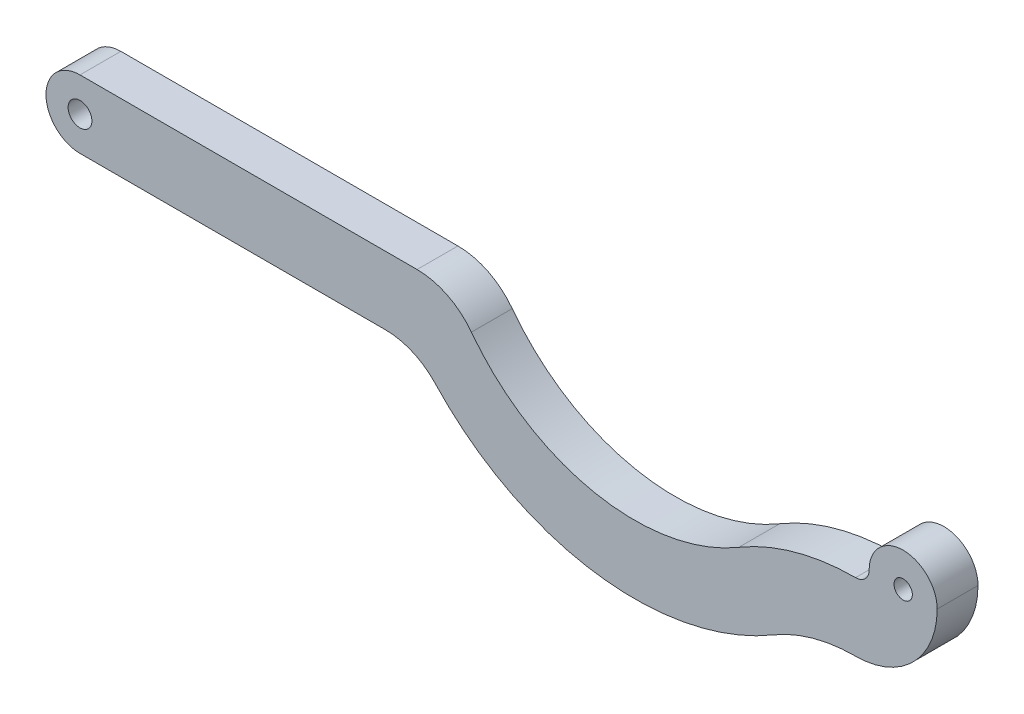
SolidWorks part; units mm, degrees
ref_plane "Plan de face" through (0, 0, 0) normal (0, 0, 1) x (1, 0, 0)
ref_plane "Plan de dessus" through (0, 0, 0) normal (0, 1, 0) x (1, 0, 0)
ref_plane "Plan de droite" through (0, 0, 0) normal (1, 0, 0) x (0, 0, -1)
sketch "Esquisse1" plane through (0, 0, 0) normal (0, 0, 1) x (1, 0, 0)
  line L0 (113.4531, 0) -> (121, 0) construction
  line L1 (0, 0) -> (49.5469, 0)
  line L2 (0, 0) -> (0, 10) construction
  line L3 (0, 10) -> (55, 10)
  line L4 (121, 0) -> (121, 10) construction
  line L5 (108, 10) -> (121, 10) construction
  line L6 (121, 5) -> (116, 5) construction
  line L7 (114, 3) -> (114, -7) construction
  arc A0 (0, 10) -> (0, 0) centre (0, 5) ccw
  arc A1 (121, 10) -> (126, 5) centre (121, 5) cw
  circle A2 centre (0, 5) radius 1.75
  circle A3 centre (121, 5) radius 1.35
  arc A4 (49.5469, 0) -> (101.9535, -10.3128) centre (81.5, 24.0624) ccw
  arc A5 (55, 10) -> (96.8401, -1.719) centre (81.5, 24.0624) ccw
  arc A6 (121, 10) -> (116, 5) centre (121, 5) ccw
  arc A7 (116, 5) -> (114, 3) centre (114, 5) cw
  arc A8 (96.8401, -1.719) -> (114, 3) centre (114, -30.5589) cw
  arc A9 (126, 5) -> (114, -7) centre (114, 5) cw
  arc A10 (114, -7) -> (101.9535, -10.3128) centre (114, -30.5588) ccw
  arc A11 (96.8401, -1.719) -> (108, 10) centre (81.5, 24.0624) ccw construction
  arc A12 (114, 0.7439) -> (113.4531, 0) centre (81.5, 24.0624) ccw construction
  arc A13 (101.9535, -10.3128) -> (114, 0.7439) centre (81.5, 24.0624) ccw construction
  arc A14 (126, 5) -> (121, 0) centre (121, 5) cw construction
  point P25 (98.691, -12.0551)
  dimension "D3" = 3.5
  dimension "D5" = 10
  dimension "D6" = 30
  dimension "D8" = 2.7
  dimension "D1" = 10
  dimension "D2" = 121
  dimension "D4" = 13
  dimension "D7" = 55
  dimension "D9" = 10
  dimension "D10" = 2
extrude "Boss.-Extru.1" add sketch "Esquisse1" along normal blind 6
chamfer "Chanfrein1" distance 1.25 angle 45 2 edges at (1.75, 5, 0) (122.35, 5, 0)
fillet "Congé1" radius 10 2 edges at (49.5469, 0, 3) (55, 10, 3)
